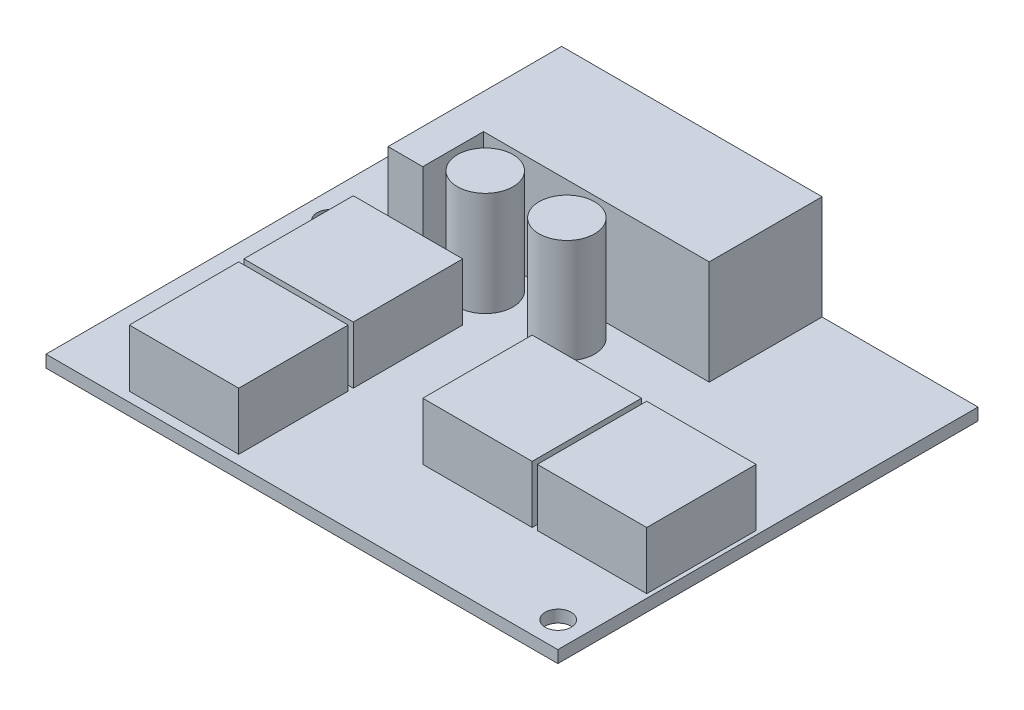
SolidWorks part; units mm, degrees
ref_plane "Front Plane" through (0, 0, 0) normal (0, 0, 1) x (1, 0, 0)
ref_plane "Top Plane" through (0, 0, 0) normal (0, 1, 0) x (1, 0, 0)
ref_plane "Right Plane" through (0, 0, 0) normal (1, 0, 0) x (0, 0, -1)
sketch "Sketch1" plane through (0, 0, 0) normal (0, 1, 0) x (1, 0, 0)
  line L1 (0, 0) -> (37.4396, 0)
  line L2 (0, 0) -> (0, 30.734)
  line L3 (0, 30.734) -> (37.4396, 30.734)
  line L4 (37.4396, 0) -> (37.4396, 30.734)
  circle A0 centre (19.939, 28.702) radius 0.9525
  circle A1 centre (35.56, 1.905) radius 0.9525
  circle A2 centre (1.905, 18.8722) radius 0.9525
  dimension "D1" = 30.734
  dimension "D2" = 37.4396
extrude "Boss-Extrude1" add sketch "Sketch1" along normal blind 0.889
sketch "Sketch2" plane through (0, 0.889, 0) normal (0, 1, 0) x (1, 0, 0)
  circle A0 centre (12.065, 20.066) radius 2.032
  circle A1 centre (18.034, 20.066) radius 2.032
extrude "Boss-Extrude2" add sketch "Sketch2" along normal blind 7.62
sketch "Sketch3" plane through (0, 0.889, 0) normal (0, 1, 0) x (1, 0, 0)
  line L0 (37.4396, 30.734) -> (0, 30.734) construction
  line L1 (6.985, 18.034) -> (9.525, 18.034)
  line L2 (6.985, 18.034) -> (6.985, 30.734)
  line L3 (6.985, 30.734) -> (9.525, 30.734)
  line L4 (9.525, 18.034) -> (9.525, 30.734)
  line L5 (9.525, 30.734) -> (26.035, 30.734)
  line L6 (9.525, 30.734) -> (9.525, 22.479)
  line L7 (9.525, 22.479) -> (26.035, 22.479)
  line L8 (26.035, 30.734) -> (26.035, 22.479)
  line L9 (0, 30.734) -> (0, 0) construction
  line M11 (37.4396, 30.734) -> (0, 30.734)
  circle M12 centre (19.939, 28.702) radius 0.9525
  dimension "D1" = 12.7
  dimension "D2" = 0
  dimension "D3" = 8.255
  dimension "D4" = 16.51
  dimension "D5" = 2.54
  dimension "D6" = 6.985
extrude "Boss-Extrude4" add sketch "Sketch3" along normal blind 7.62 contours L8 L4 L7 M11 M12 | M12 | L1 L4 L2 M11
sketch "Sketch4" plane through (0, 0.889, 0) normal (0, 1, 0) x (1, 0, 0)
  line L1 (20.7645, 14.7955) -> (28.7655, 14.7955)
  line L2 (20.7645, 14.7955) -> (20.7645, 6.7945)
  line L3 (20.7645, 6.7945) -> (28.7655, 6.7945)
  line L4 (28.7655, 14.7955) -> (28.7655, 6.7945)
  line L5 (29.1465, 14.7955) -> (37.1475, 14.7955)
  line L6 (29.1465, 14.7955) -> (29.1465, 6.7945)
  line L7 (29.1465, 6.7945) -> (37.1475, 6.7945)
  line L8 (37.1475, 14.7955) -> (37.1475, 6.7945)
  line L9 (5.3975, 8.6995) -> (13.3985, 8.6995)
  line L10 (5.3975, 8.6995) -> (5.3975, 0.6985)
  line L11 (5.3975, 0.6985) -> (13.3985, 0.6985)
  line L12 (13.3985, 8.6995) -> (13.3985, 0.6985)
  line L13 (5.3975, 17.0815) -> (13.3985, 17.0815)
  line L14 (5.3975, 17.0815) -> (5.3975, 9.0805)
  line L15 (5.3975, 9.0805) -> (13.3985, 9.0805)
  line L16 (13.3985, 17.0815) -> (13.3985, 9.0805)
  point P16 (9.398, 13.081)
  point P17 (9.398, 4.699)
  point P18 (24.765, 10.795)
  point P19 (33.147, 10.795)
  dimension "D1" = 8.001
  dimension "D2" = 8.001
  dimension "D3" = 8.001
  dimension "D4" = 8.001
  dimension "D5" = 4.0005
  dimension "D6" = 4.0005
  dimension "D7" = 4.0005
  dimension "D8" = 4.0005
  dimension "D9" = 8.001
  dimension "D10" = 8.001
  dimension "D11" = 8.001
  dimension "D12" = 8.001
  dimension "D13" = 4.0005
  dimension "D14" = 4.0005
  dimension "D15" = 4.0005
  dimension "D16" = 4.0005
extrude "Boss-Extrude5" add sketch "Sketch4" along normal blind 4.191
